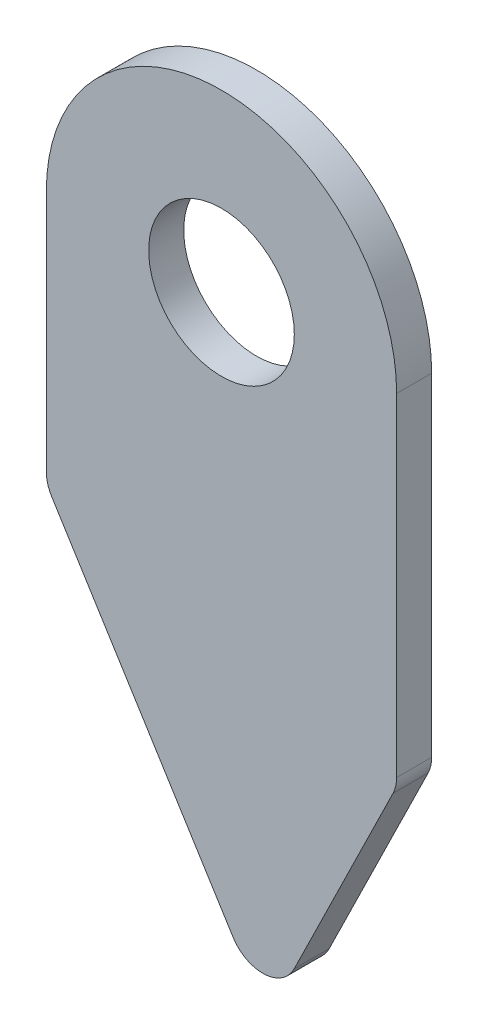
SolidWorks part; units mm, degrees
material "ASTM A36 Steel"
ref_plane "X-Y Datum" through (0, 0, 0) normal (0, 0, 1) x (1, 0, 0)
ref_plane "X-Z Datum" through (0, 0, 0) normal (0, 1, 0) x (1, 0, 0)
ref_plane "Y-Z Datum" through (0, 0, 0) normal (1, 0, 0) x (0, 0, -1)
sketch "Sketch1" plane through (0, 0, 0) normal (0, 0, 1) x (1, 0, 0)
  line L0 (-7.9375, 0) -> (-7.9375, -28.575)
  line L1 (-7.9375, -28.575) -> (7.9375, -28.575)
  line L2 (7.9375, -28.575) -> (7.9375, 0)
  circle A0 centre (0, 0) radius 7.9375
  circle A1 centre (0, 0) radius 3
  dimension "D1" = 6
  dimension "D2" = 15.875
  dimension "D3" = 28.575
extrude "Boss-Extrude1" add sketch "Sketch1" along normal blind 1.5875 contours A0 A1 | A0 L0 L1 L2 | A1
hole_wizard "M6 Clearance Hole1" positions "Sketch2" profile "Sketch3" hole size "M6" standard "ANSI Metric" end condition through all
sketch "Sketch2" plane through (0, 0, 1.5875) normal (0, 0, 1) x (1, 0, 0)
  point P0 (0, 0)
sketch "Sketch3" plane through (0, 0, 1.5875) normal (1, 0, 0) x (0, -1, 0)
  line L0 (0, 0) -> (0, 1.5875)
  line L1 (0, 1.5875) -> (3.3, 1.5875)
  line L2 (3.3, 1.5875) -> (3.3, 0)
  line L5 (3.3, 0) -> (0, 0)
  line L11 (0, -6.35) -> (0, 107.95) construction
  dimension "Thru Hole Dia." = 6.6
  dimension "Thru Hole Depth" = 1.5875
sketch "Sketch4" plane through (0, 0, 1.5875) normal (0, 0, 1) x (1, 0, 0)
  line L0 (1.3788, -19.2148) -> (-109.9479, 159.3138) construction
  line L1 (1.3788, -19.2148) -> (-109.9479, 159.3138) construction
  line L2 (6.4838, -27.4013) -> (-109.9479, 159.3138) construction
  line L3 (55.1899, 89.5082) -> (-10.3661, -44.0945) construction
  line L4 (55.1899, 89.5082) -> (-10.3661, -44.0945) construction
  line L5 (5.9742, -33.7846) -> (-113.1808, 157.2978)
  line L6 (58.6569, 87.9249) -> (-6.9456, -45.7728)
  line L7 (-1.8541, -21.2308) -> (-113.1808, 157.2978) construction
  line L8 (58.6103, 87.8299) -> (-6.9456, -45.7728) construction
  point P8 (6.4838, -27.4013)
  point P12 (5.3887, -34.1497)
  point P13 (59.2764, 87.6211)
  line M3 (-7.9375, 0) -> (-7.9375, -28.575)
  line M4 (-7.9375, -28.575) -> (7.9375, -28.575)
  line M5 (7.9375, -28.575) -> (7.9375, 0)
  dimension "D1" = 3.81
extrude "Cut-Extrude1" cut sketch "Sketch4" against normal through all contours L5 M4 M3 | L6 M5 M4 | L5 L6 M4
sketch "Sketch5" [suppressed] plane through (0, 0, 1.5875) normal (0, 0, 1) x (1, 0, 0)
  line L0 (-7.9375, 0) -> (-7.9375, -28.575) construction
  line L1 (7.9375, -28.575) -> (-7.9375, -28.575)
  line L2 (7.9375, -28.575) -> (7.9375, -22.225)
  line L3 (7.9375, -22.225) -> (-7.9375, -22.225)
  line L4 (-7.9375, -28.575) -> (-7.9375, -22.225)
  dimension "D1" = 6.35
extrude "Cut-Extrude2" [suppressed] cut sketch "Sketch5" against normal through all
sketch "Sketch6" [suppressed] plane through (0, 0, 0) normal (0, 0, -1) x (-1, 0, 0)
  spline S0 degree 3 poles (11.1636, -26.4867) (3.0884, -2.4046) (-38.3742, -16.3077) (-30.299, -40.3899) (-22.2238, -64.4721) (19.2388, -50.5689) (11.1636, -26.4867) (3.0884, -2.4046) (-38.3742, -16.3077) knots -0.5 0 0 0 0.5 0.5 0.5 1 1 1 1.5 1.5 1.5 weights 1 0.333333 0.333333 1 0.333333 0.333333 1 0.333333 0.333333 only from (11.1636, -26.4867) to (11.1636, -26.4867)
  spline S1 degree 3 poles (11.1636, -26.4867) (3.0884, -2.4046) (-38.3742, -16.3077) (-30.299, -40.3899) (-22.2238, -64.4721) (19.2388, -50.5689) (11.1636, -26.4867) (3.0884, -2.4046) (-38.3742, -16.3077) knots -0.5 0 0 0 0.5 0.5 0.5 1 1 1 1.5 1.5 1.5 weights 1 0.333333 0.333333 1 0.333333 0.333333 1 0.333333 0.333333 only from (11.1636, -26.4867) to (11.1636, -26.4867)
extrude "Cut-Extrude3" [suppressed] cut sketch "Sketch6" against normal through all
fillet "Fillet1" radius 1.5875 3 edges at (7.9375, -15.441, 0.7937) (-7.9375, -11.4752, 0.7937) (2.0357, -27.4688, 0.7937)
fillet "Fillet2" [suppressed] radius 1.5875
fillet "Fillet3" [suppressed] radius 1.5875
